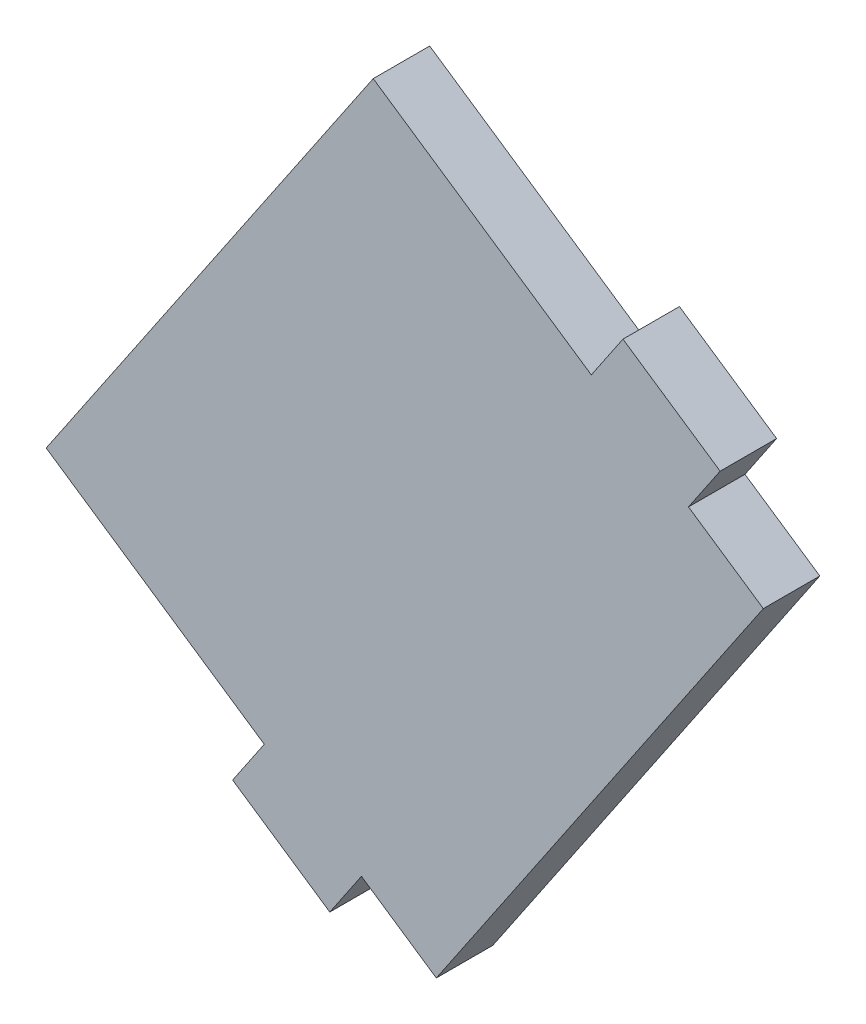
SolidWorks part; units mm, degrees
ref_plane "Front" through (0, 0, 0) normal (0, 0, 1) x (1, 0, 0)
ref_plane "Top" through (0, 0, 0) normal (0, 1, 0) x (1, 0, 0)
ref_plane "Right" through (0, 0, 0) normal (1, 0, 0) x (0, 0, -1)
sketch "Sketch1" plane through (0, 0, 0) normal (0, 0, 1) x (1, 0, 0)
  line L0 (596.8812, 476.9604) -> (614.2512, 502.637)
  line L1 (617.6025, 462.9426) -> (634.9725, 488.6192)
  line L2 (608.4651, 469.124) -> (596.8812, 476.9604)
  line L3 (606.7842, 466.6392) -> (608.4651, 469.124)
  line L4 (611.9458, 463.1473) -> (613.6268, 465.6322)
  line L5 (611.9458, 463.1473) -> (606.7842, 466.6392)
  line L6 (617.6025, 462.9426) -> (613.6268, 465.6322)
  line L7 (625.8351, 494.8005) -> (614.2512, 502.637)
  line L8 (632.6777, 493.7935) -> (627.5161, 497.2853)
  line L9 (625.8351, 494.8005) -> (627.5161, 497.2853)
  line L10 (630.9967, 491.3087) -> (632.6777, 493.7935)
  line L11 (634.9725, 488.6192) -> (630.9967, 491.3087)
  dimension "D1" = 6.2318
  dimension "D2" = 4.8
extrude "Base-Extrude" add sketch "Sketch1" along normal blind 3
